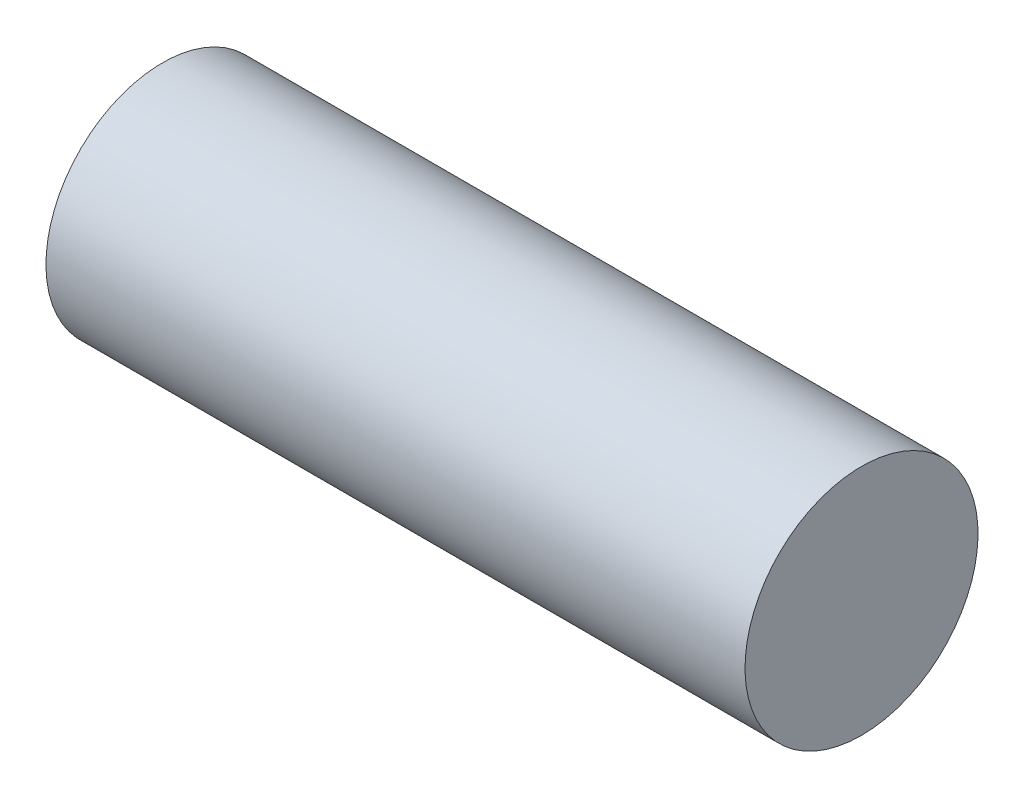
SolidWorks part; units mm, degrees
ref_plane "Plane1" through (0, 0, 0) normal (0, 0, 1) x (1, 0, 0)
ref_plane "Plane2" through (0, 0, 0) normal (0, 1, 0) x (1, 0, 0)
ref_plane "Plane3" through (0, 0, 0) normal (1, 0, 0) x (0, 0, -1)
sketch "BodySke" plane through (0, 0, 0) normal (0, 0, 1) x (1, 0, 0)
  line L0 (0, 0) -> (40.9091, 0) construction
  line L2 (0, 5) -> (30, 5)
  line L3 (30, 5) -> (30, 0)
  line L4 (0, 0) -> (30, 0)
  line L6 (0, 5) -> (0, 0)
  dimension "Diameter" = 10
  dimension "Length" = 30
revolve "Body" add sketch "BodySke" angle 360 about L0
